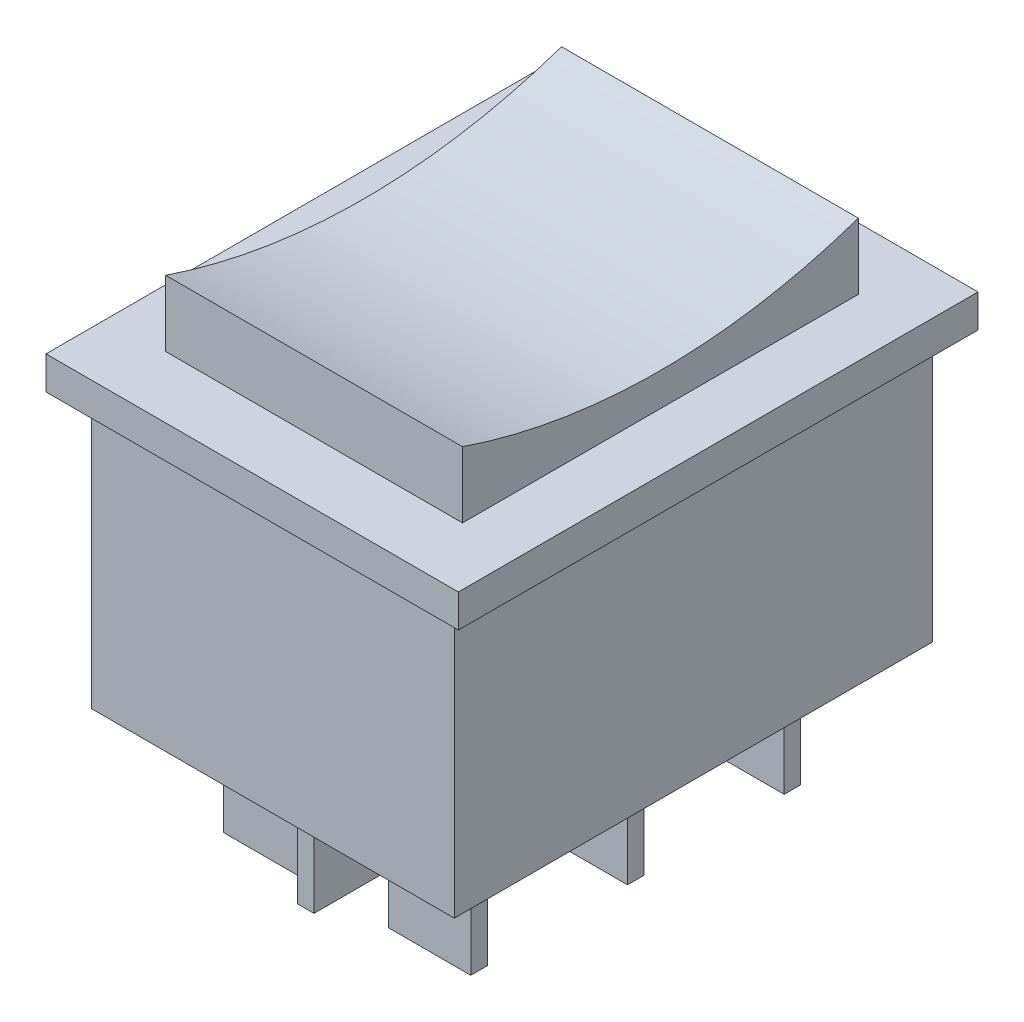
SolidWorks part; units mm, degrees
material "ABS"
ref_plane "Ebene vorne" through (0, 0, 0) normal (0, 0, 1) x (1, 0, 0)
ref_plane "Ebene oben" through (0, 0, 0) normal (0, 1, 0) x (1, 0, 0)
ref_plane "Ebene rechts" through (0, 0, 0) normal (1, 0, 0) x (0, 0, -1)
sketch "Skizze1" plane through (0, 0, 0) normal (0, 1, 0) x (1, 0, 0)
  line L1 (-12.5, 15.75) -> (12.5, 15.75)
  line L2 (-12.5, 15.75) -> (-12.5, -15.75)
  line L3 (-12.5, -15.75) -> (12.5, -15.75)
  line L4 (12.5, 15.75) -> (12.5, -15.75)
  line L5 (-12.5, 15.75) -> (12.5, -15.75) construction
  line L6 (-12.5, -15.75) -> (12.5, 15.75) construction
  point P0 (0, 0)
  dimension "D1" = 25
  dimension "D2" = 31.5
extrude "Aufsatz-Linear austragen1" add sketch "Skizze1" along normal blind 2
sketch "Skizze2" plane through (0, 0, 0) normal (0, -1, 0) x (1, 0, 0)
  line L1 (-11, 14.5) -> (11, 14.5)
  line L2 (-11, 14.5) -> (-11, -14.5)
  line L3 (-11, -14.5) -> (11, -14.5)
  line L4 (11, 14.5) -> (11, -14.5)
  line L5 (-11, 14.5) -> (11, -14.5) construction
  line L6 (-11, -14.5) -> (11, 14.5) construction
  point P0 (0, 0)
  dimension "D1" = 22
  dimension "D2" = 29
extrude "Aufsatz-Linear austragen2" add sketch "Skizze2" along normal blind 16.5
sketch "Skizze3" plane through (0, -16.5, 0) normal (0, -1, 0) x (1, 0, 0)
  line L1 (-0.5, 12.5) -> (0.5, 12.5)
  line L2 (-0.5, 12.5) -> (-0.5, -12.5)
  line L3 (-0.5, -12.5) -> (0.5, -12.5)
  line L4 (0.5, 12.5) -> (0.5, -12.5)
  line L5 (-0.5, 12.5) -> (0.5, -12.5) construction
  line L6 (-0.5, -12.5) -> (0.5, 12.5) construction
  point P0 (0, 0)
  dimension "D1" = 25
  dimension "D2" = 1
extrude "Aufsatz-Linear austragen3" add sketch "Skizze3" along normal blind 6
sketch "Skizze4" plane through (0, -16.5, 0) normal (0, -1, 0) x (1, 0, 0)
  line L1 (-5, 9.5) -> (5, 9.5) construction
  line L2 (-5, 9.5) -> (-5, -9.5) construction
  line L3 (-5, -9.5) -> (5, -9.5) construction
  line L4 (5, 9.5) -> (5, -9.5) construction
  line L5 (-5, 9.5) -> (5, -9.5) construction
  line L6 (-5, -9.5) -> (5, 9.5) construction
  line L7 (-7.5, 9) -> (-2.5, 9)
  line L8 (-7.5, 9) -> (-7.5, 10)
  line L9 (-7.5, 10) -> (-2.5, 10)
  line L10 (-2.5, 9) -> (-2.5, 10)
  line L11 (-7.5, 9) -> (-2.5, 10) construction
  line L12 (-7.5, 10) -> (-2.5, 9) construction
  line L13 (-2.5, -0.5) -> (-7.5, -0.5)
  line L14 (-2.5, -0.5) -> (-2.5, 0.5)
  line L15 (-2.5, 0.5) -> (-7.5, 0.5)
  line L16 (-7.5, -0.5) -> (-7.5, 0.5)
  line L17 (-2.5, -0.5) -> (-7.5, 0.5) construction
  line L18 (-2.5, 0.5) -> (-7.5, -0.5) construction
  line L19 (-7.5, -9) -> (-2.5, -9)
  line L20 (-7.5, -9) -> (-7.5, -10)
  line L21 (-7.5, -10) -> (-2.5, -10)
  line L22 (-2.5, -9) -> (-2.5, -10)
  line L23 (-7.5, -9) -> (-2.5, -10) construction
  line L24 (-7.5, -10) -> (-2.5, -9) construction
  line L25 (7.5, -10) -> (2.5, -10)
  line L26 (7.5, -10) -> (7.5, -9)
  line L27 (7.5, -9) -> (2.5, -9)
  line L28 (2.5, -10) -> (2.5, -9)
  line L29 (7.5, -10) -> (2.5, -9) construction
  line L30 (7.5, -9) -> (2.5, -10) construction
  line L31 (2.5, -0.5) -> (7.5, -0.5)
  line L32 (2.5, -0.5) -> (2.5, 0.5)
  line L33 (2.5, 0.5) -> (7.5, 0.5)
  line L34 (7.5, -0.5) -> (7.5, 0.5)
  line L35 (2.5, -0.5) -> (7.5, 0.5) construction
  line L36 (2.5, 0.5) -> (7.5, -0.5) construction
  line L37 (7.5, 9) -> (2.5, 9)
  line L38 (7.5, 9) -> (7.5, 10)
  line L39 (7.5, 10) -> (2.5, 10)
  line L40 (2.5, 9) -> (2.5, 10)
  line L41 (7.5, 9) -> (2.5, 10) construction
  line L42 (7.5, 10) -> (2.5, 9) construction
  point P0 (0, 0)
  point P10 (-5, 0)
  point P23 (5, 0)
  dimension "D1" = 5
  dimension "D2" = 1
  dimension "D3" = 19
  dimension "D4" = 10
extrude "Aufsatz-Linear austragen4" add sketch "Skizze4" along normal blind 7
sketch "Skizze5" plane through (0, 2, 0) normal (0, 1, 0) x (1, 0, 0)
  line L1 (-9, 12) -> (9, 12)
  line L2 (-9, 12) -> (-9, -12)
  line L3 (-9, -12) -> (9, -12)
  line L4 (9, 12) -> (9, -12)
  line L5 (-9, 12) -> (9, -12) construction
  line L6 (-9, -12) -> (9, 12) construction
  point P0 (0, 0)
  dimension "D1" = 24
  dimension "D2" = 18
extrude "Aufsatz-Linear austragen5" add sketch "Skizze5" along normal blind 4
sketch "Skizze6" plane through (-9, 0, 0) normal (-1, 0, 0) x (0, 0, 1)
  line L0 (0, 6) -> (0, 41) construction
  line L1 (-12, 6) -> (12, 6) construction
  line L3 (0, 4) -> (0, 2) construction
  line L4 (-15.75, 2) -> (15.75, 2) construction
  circle A0 centre (0, 41) radius 37
  dimension "D1" = 2
extrude "Schnitt-Linear austragen1" cut sketch "Skizze6" against normal through all
